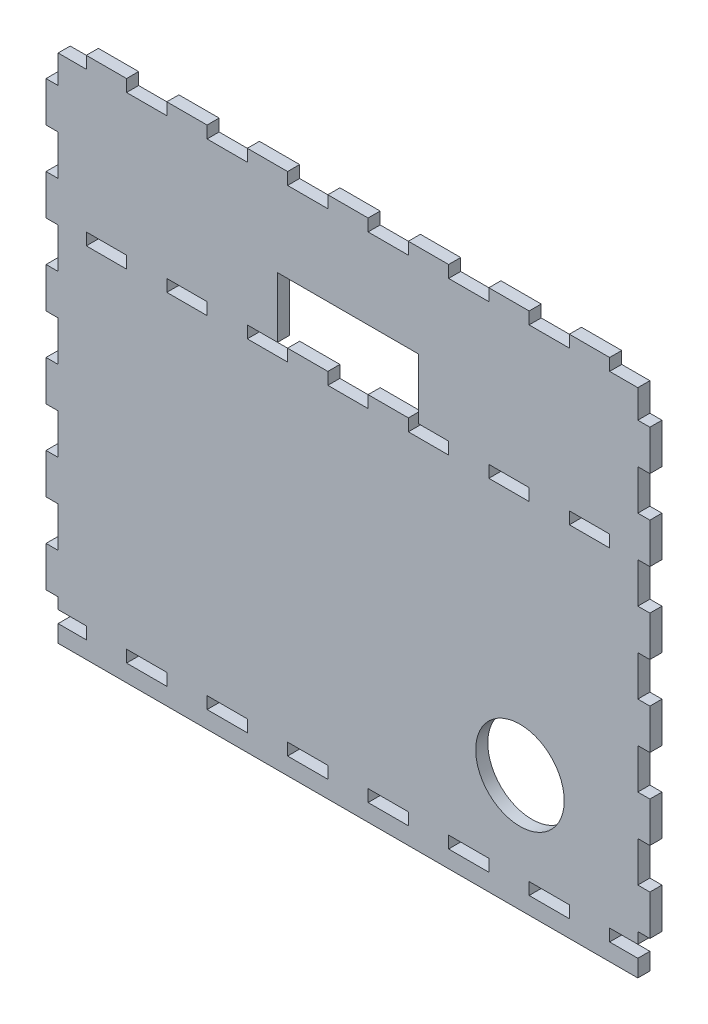
SolidWorks part; units mm, degrees
ref_plane "Alzado" through (0, 0, 0) normal (0, 0, 1) x (1, 0, 0)
ref_plane "Planta" through (0, 0, 0) normal (0, 1, 0) x (1, 0, 0)
ref_plane "Vista lateral" through (0, 0, 0) normal (1, 0, 0) x (0, 0, -1)
sketch "Croquis1" plane through (0, 0, 0) normal (0, 0, 1) x (1, 0, 0)
  line L0 (-45, 71.5) -> (-45, 68.5)
  line L1 (-72, -68.5) -> (72, -68.5)
  line L2 (-72, -58.5) -> (-72, -48.5)
  line L3 (-72, 68.5) -> (-65, 68.5)
  line L4 (72, -58.5) -> (72, -48.5)
  line L5 (-72, -68.5) -> (72, 68.5) construction
  line L6 (-72, 68.5) -> (72, -68.5) construction
  line L7 (-65, 71.5) -> (-55, 71.5)
  line L8 (-65, 71.5) -> (-65, 68.5)
  line L10 (-55, 71.5) -> (-55, 68.5)
  line L11 (-45, 71.5) -> (-35, 71.5)
  line L12 (-35, 71.5) -> (-35, 68.5)
  line L14 (-25, 71.5) -> (-25, 68.5)
  line L15 (-25, 71.5) -> (-15, 71.5)
  line L16 (-15, 71.5) -> (-15, 68.5)
  line L18 (-5, 71.5) -> (-5, 68.5)
  line L19 (-5, 71.5) -> (5, 71.5)
  line L20 (5, 71.5) -> (5, 68.5)
  line L22 (15, 71.5) -> (15, 68.5)
  line L23 (15, 71.5) -> (25, 71.5)
  line L24 (25, 71.5) -> (25, 68.5)
  line L26 (35, 71.5) -> (35, 68.5)
  line L27 (35, 71.5) -> (45, 71.5)
  line L28 (45, 71.5) -> (45, 68.5)
  line L30 (55, 71.5) -> (55, 68.5)
  line L31 (55, 71.5) -> (65, 71.5)
  line L32 (65, 71.5) -> (65, 68.5)
  line L35 (-72, 61.5) -> (-75, 61.5)
  line L37 (-72, 51.5) -> (-75, 51.5)
  line L38 (-75, 61.5) -> (-75, 51.5)
  line L58 (0, 0) -> (0, 41.2276) construction
  line L83 (-55, -51.25) -> (-55, -54.25)
  line L84 (-75, -51.25) -> (-65, -51.25)
  line L85 (-75, -51.25) -> (-75, -54.25)
  line L86 (-75, -54.25) -> (-65, -54.25)
  line L87 (-65, -51.25) -> (-65, -54.25)
  line L88 (-55, -51.25) -> (-45, -51.25)
  line L89 (-45, -51.25) -> (-45, -54.25)
  line L90 (-55, -54.25) -> (-45, -54.25)
  line L91 (-35, -51.25) -> (-35, -54.25)
  line L92 (-35, -51.25) -> (-25, -51.25)
  line L93 (-25, -51.25) -> (-25, -54.25)
  line L94 (-35, -54.25) -> (-25, -54.25)
  line L95 (-15, -51.25) -> (-15, -54.25)
  line L96 (-15, -51.25) -> (-5, -51.25)
  line L97 (-5, -51.25) -> (-5, -54.25)
  line L98 (-15, -54.25) -> (-5, -54.25)
  line L99 (5, -51.25) -> (5, -54.25)
  line L100 (5, -51.25) -> (15, -51.25)
  line L101 (15, -51.25) -> (15, -54.25)
  line L102 (5, -54.25) -> (15, -54.25)
  line L103 (25, -51.25) -> (25, -54.25)
  line L104 (25, -51.25) -> (35, -51.25)
  line L105 (35, -51.25) -> (35, -54.25)
  line L106 (25, -54.25) -> (35, -54.25)
  line L107 (45, -51.25) -> (45, -54.25)
  line L108 (45, -51.25) -> (55, -51.25)
  line L109 (55, -51.25) -> (55, -54.25)
  line L110 (45, -54.25) -> (55, -54.25)
  line L111 (65, -51.25) -> (65, -54.25)
  line L112 (65, -51.25) -> (75, -51.25)
  line L113 (75, -51.25) -> (75, -54.25)
  line L114 (65, -54.25) -> (75, -54.25)
  line L115 (-45, 33.5) -> (-45, 30.5)
  line L116 (-65, 33.5) -> (-55, 33.5)
  line L117 (-65, 33.5) -> (-65, 30.5)
  line L118 (-65, 30.5) -> (-55, 30.5)
  line L119 (-55, 33.5) -> (-55, 30.5)
  line L120 (-45, 33.5) -> (-35, 33.5)
  line L121 (-35, 33.5) -> (-35, 30.5)
  line L122 (-45, 30.5) -> (-35, 30.5)
  line L123 (-25, 33.5) -> (-25, 30.5)
  line L124 (-25, 33.5) -> (-15, 33.5)
  line L125 (-15, 33.5) -> (-15, 30.5)
  line L126 (-25, 30.5) -> (-15, 30.5)
  line L127 (-5, 33.5) -> (-5, 30.5)
  line L128 (-5, 33.5) -> (5, 33.5)
  line L129 (5, 33.5) -> (5, 30.5)
  line L130 (-5, 30.5) -> (5, 30.5)
  line L131 (15, 33.5) -> (15, 30.5)
  line L132 (15, 33.5) -> (25, 33.5)
  line L133 (25, 33.5) -> (25, 30.5)
  line L134 (15, 30.5) -> (25, 30.5)
  line L135 (35, 33.5) -> (35, 30.5)
  line L136 (35, 33.5) -> (45, 33.5)
  line L137 (45, 33.5) -> (45, 30.5)
  line L138 (35, 30.5) -> (45, 30.5)
  line L139 (55, 33.5) -> (55, 30.5)
  line L140 (55, 33.5) -> (65, 33.5)
  line L141 (65, 33.5) -> (65, 30.5)
  line L142 (55, 30.5) -> (65, 30.5)
  line L144 (-17.5, 48.5) -> (17.5, 48.5)
  line L145 (-17.5, 48.5) -> (-17.5, 33.5)
  line L146 (-17.5, 33.5) -> (17.5, 33.5)
  line L147 (17.5, 48.5) -> (17.5, 33.5)
  line L148 (-17.5, 48.5) -> (17.5, 33.5) construction
  line L149 (-17.5, 33.5) -> (17.5, 48.5) construction
  line L174 (-72, 41.5) -> (-75, 41.5)
  line L175 (-75, 41.5) -> (-75, 31.5)
  line L176 (-72, 31.5) -> (-75, 31.5)
  line L178 (-72, 21.5) -> (-75, 21.5)
  line L179 (-75, 21.5) -> (-75, 11.5)
  line L180 (-72, 11.5) -> (-75, 11.5)
  line L182 (-72, 1.5) -> (-75, 1.5)
  line L183 (-75, 1.5) -> (-75, -8.5)
  line L184 (-72, -8.5) -> (-75, -8.5)
  line L186 (-72, -18.5) -> (-75, -18.5)
  line L187 (-75, -18.5) -> (-75, -28.5)
  line L188 (-72, -28.5) -> (-75, -28.5)
  line L190 (-72, -38.5) -> (-75, -38.5)
  line L191 (-75, -38.5) -> (-75, -48.5)
  line L192 (-72, -48.5) -> (-75, -48.5)
  line L194 (-72, -58.5) -> (-75, -58.5)
  line L195 (-75, -58.5) -> (-75, -68.5)
  line L196 (-72, -68.5) -> (-75, -68.5)
  line L197 (72, -58.5) -> (75, -58.5)
  line L198 (75, -58.5) -> (75, -68.5)
  line L199 (72, -68.5) -> (75, -68.5)
  line L201 (72, -38.5) -> (75, -38.5)
  line L202 (75, -38.5) -> (75, -48.5)
  line L203 (72, -48.5) -> (75, -48.5)
  line L205 (72, -18.5) -> (75, -18.5)
  line L206 (75, -18.5) -> (75, -28.5)
  line L207 (72, -28.5) -> (75, -28.5)
  line L209 (72, 1.5) -> (75, 1.5)
  line L210 (75, 1.5) -> (75, -8.5)
  line L211 (72, -8.5) -> (75, -8.5)
  line L213 (72, 21.5) -> (75, 21.5)
  line L214 (75, 21.5) -> (75, 11.5)
  line L215 (72, 11.5) -> (75, 11.5)
  line L217 (72, 41.5) -> (75, 41.5)
  line L218 (75, 41.5) -> (75, 31.5)
  line L219 (72, 31.5) -> (75, 31.5)
  line L221 (72, 51.5) -> (75, 51.5)
  line L222 (75, 61.5) -> (75, 51.5)
  line L223 (72, 61.5) -> (75, 61.5)
  line L225 (-55, 68.5) -> (-45, 68.5)
  line L226 (-35, 68.5) -> (-25, 68.5)
  line L227 (-15, 68.5) -> (-5, 68.5)
  line L228 (5, 68.5) -> (15, 68.5)
  line L229 (25, 68.5) -> (35, 68.5)
  line L230 (45, 68.5) -> (55, 68.5)
  line L231 (65, 68.5) -> (72, 68.5)
  line L232 (72, 61.5) -> (72, 68.5)
  line L233 (72, 41.5) -> (72, 51.5)
  line L234 (72, 21.5) -> (72, 31.5)
  line L235 (72, 1.5) -> (72, 11.5)
  line L236 (72, -18.5) -> (72, -8.5)
  line L237 (72, -38.5) -> (72, -28.5)
  line L238 (-72, -58.5) -> (72, -58.5)
  line L239 (-72, -38.5) -> (-72, -28.5)
  line L241 (-72, -18.5) -> (-72, -8.5)
  line L243 (-72, 1.5) -> (-72, 11.5)
  line L245 (-72, 21.5) -> (-72, 31.5)
  line L247 (-72, 41.5) -> (-72, 51.5)
  line L249 (-72, 61.5) -> (-72, 68.5)
  circle A0 centre (42.7259, -29.5296) radius 11
  point P0 (0, 0)
  point P39 (-65, -52.75)
  point P120 (0, 41)
  dimension "D8" = 22
  dimension "D1" = 144
  dimension "D2" = 137
  dimension "D3" = 10
  dimension "D4" = 3
  dimension "D5" = 7
  dimension "D7" = 10
  dimension "D9" = 3
  dimension "D10" = 10
  dimension "D12" = 10
  dimension "D13" = 10
  dimension "D14" = 3
  dimension "D16" = 14.25
  dimension "D17" = 10
  dimension "D18" = 10
  dimension "D19" = 3
  dimension "D20" = 7
  dimension "D22" = 10
  dimension "D23" = 35
  dimension "D24" = 15
  dimension "D25" = 35
  dimension "D26" = 7
  dimension "D6" = 7
  dimension "D15" = 8
  dimension "D21" = 7
  dimension "D11" = 7
extrude "Saliente-Extruir1" add sketch "Croquis1" along normal blind 3 contours L249 L35 L38 L37 L247 L174 L175 L176 L245 L178 L179 L180 L243 L182 L183 L184 L241 L186 L187 L188 L239 L190 L191 L192 L2 L84 L87 L86 L194 L195 L196 L1 L199 L198 L197 L4 L114 L111 L112 L203 L202 L201 L237 L207 L206 L205 L236 L211 L210
